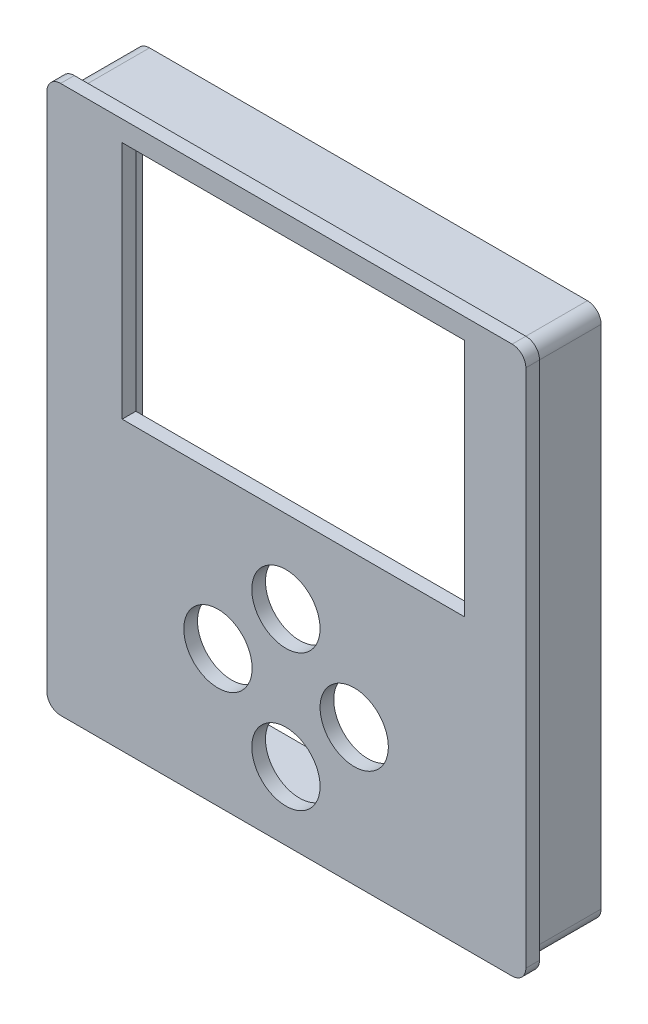
SolidWorks part; units mm, degrees
ref_plane "Front Plane" through (0, 0, 0) normal (0, 0, 1) x (1, 0, 0)
ref_plane "Top Plane" through (0, 0, 0) normal (0, 1, 0) x (1, 0, 0)
ref_plane "Right Plane" through (0, 0, 0) normal (1, 0, 0) x (0, 0, -1)
sketch "Sketch1" plane through (0, 0, 0) normal (0, 0, 1) x (1, 0, 0)
  line L0 (2.54, 0) -> (86.36, 0)
  line L1 (0, 2.54) -> (0, 99.06)
  line L2 (2.54, 101.6) -> (86.36, 101.6)
  line L3 (88.9, 99.06) -> (88.9, 2.54)
  line L20 (13.97, 97.79) -> (13.97, 53.34)
  line L21 (13.97, 53.34) -> (77.47, 53.34)
  line L22 (77.47, 53.34) -> (77.47, 97.79)
  line L23 (77.47, 97.79) -> (13.97, 97.79)
  circle A0 centre (44.3666, 38.0285) radius 6.3381
  circle A1 centre (57.0428, 25.3523) radius 6.3381
  circle A2 centre (57.0428, 25.3523) radius 6.3381
  circle A3 centre (44.3666, 12.6762) radius 6.3381
  arc A4 (2.54, 0) -> (0, 2.54) centre (2.54, 2.54) cw
  arc A5 (86.36, 0) -> (88.9, 2.54) centre (86.36, 2.54) ccw
  arc A6 (2.54, 101.6) -> (0, 99.06) centre (2.54, 99.06) ccw
  arc A7 (88.9, 99.06) -> (86.36, 101.6) centre (86.36, 99.06) ccw
  circle A8 centre (31.75, 25.3523) radius 6.3381
  point P19 (0, 0)
  point P24 (0, 101.6)
  dimension "D3" = 12.6762
  dimension "D4" = 2.54
  dimension "D5" = 2.54
  dimension "D6" = 2.54
  dimension "D7" = 2.54
  dimension "D1" = 88.9
  dimension "D2" = 101.6
  dimension "D8" = 44.3666
  dimension "D9" = 31.75
  dimension "D10" = 57.0428
  dimension "D11" = 63.5
  dimension "D12" = 44.45
  dimension "D13" = 12.6762
  dimension "D14" = 12.6762
  dimension "D15" = 12.6762
  dimension "D16" = 13.97
  dimension "D17" = 3.81
extrude "Boss-Extrude1" add sketch "Sketch1" along normal blind 2.54 contours L3 A7 L2 A6 L1 A4 L0 A5 A8 L23 L22 L21 L20 A0 A1 A3
sketch "Sketch2" plane through (0, 0, 0) normal (0, 0, -1) x (-1, 0, 0)
  line L0 (-85.09, 1.27) -> (-3.81, 1.27)
  line L1 (-1.27, 3.81) -> (-1.27, 97.79)
  line L2 (-3.81, 100.33) -> (-85.09, 100.33)
  line L3 (-87.63, 97.79) -> (-87.63, 3.81)
  line L4 (-83.82, 2.54) -> (-5.08, 2.54)
  line L5 (-2.54, 5.08) -> (-2.54, 96.52)
  line L6 (-5.08, 99.06) -> (-83.82, 99.06)
  line L7 (-86.36, 96.52) -> (-86.36, 5.08)
  line L8 (-2.54, 101.6) -> (-86.36, 101.6) construction
  line L9 (-88.9, 99.06) -> (-88.9, 2.54) construction
  line L10 (-2.54, 0) -> (-86.36, 0) construction
  arc A0 (-83.82, 2.54) -> (-86.36, 5.08) centre (-83.82, 5.08) cw
  arc A1 (-85.09, 1.27) -> (-87.63, 3.81) centre (-85.09, 3.81) cw
  arc A2 (-3.81, 1.27) -> (-1.27, 3.81) centre (-3.81, 3.81) ccw
  arc A3 (-5.08, 2.54) -> (-2.54, 5.08) centre (-5.08, 5.08) ccw
  arc A4 (-2.54, 96.52) -> (-5.08, 99.06) centre (-5.08, 96.52) ccw
  arc A5 (-1.27, 97.79) -> (-3.81, 100.33) centre (-3.81, 97.79) ccw
  arc A6 (-83.82, 99.06) -> (-86.36, 96.52) centre (-83.82, 96.52) ccw
  arc A7 (-85.09, 100.33) -> (-87.63, 97.79) centre (-85.09, 97.79) ccw
  point P19 (-2.54, 2.54)
  point P22 (-2.54, 99.06)
  point P27 (-86.36, 99.06)
  dimension "D1" = 2.54
  dimension "D2" = 2.54
  dimension "D3" = 2.54
  dimension "D4" = 2.54
  dimension "D5" = 2.54
  dimension "D6" = 2.54
  dimension "D7" = 2.54
  dimension "D8" = 2.54
  dimension "D9" = 81.28
  dimension "D10" = 1.27
  dimension "D11" = 1.27
  dimension "D12" = 1.27
extrude "Boss-Extrude2" add sketch "Sketch2" along normal blind 12.7 contours L2 A7 L3 A1 L0 A2 L1 A5 A6 L6 A4 L5 A3 L4 A0 L7
sketch "Sketch3" plane through (0, 1.27, 0) normal (0, -1, 0) x (1, 0, 0)
  line L0 (85.09, -12.7) -> (85.09, 0)
  line L1 (85.09, 0) -> (72.39, 0)
  line L2 (72.39, 0) -> (72.39, -12.7)
  line L3 (72.39, -12.7) -> (85.09, -12.7)
extrude "Cut-Extrude1" cut sketch "Sketch3" against normal up to next
